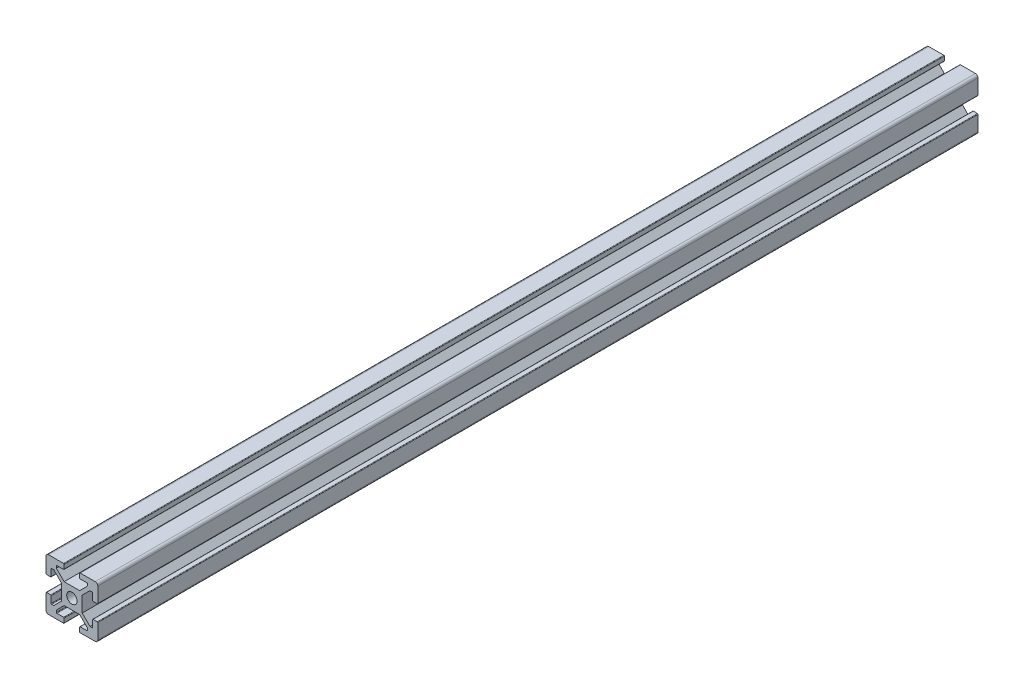
SolidWorks part; units mm, degrees
material "1060 Alloy"
ref_plane "Front Plane" through (0, 0, 0) normal (0, 0, 1) x (1, 0, 0)
ref_plane "Top Plane" through (0, 0, 0) normal (0, 1, 0) x (1, 0, 0)
ref_plane "Right Plane" through (0, 0, 0) normal (1, 0, 0) x (0, 0, -1)
sketch "Sketch1" plane through (0, 0, 0) normal (0, 0, 1) x (1, 0, 0)
  circle A28 centre (0, 0) radius 2
  point P0 (0, 0)
  line B0 (-3.2, 8) -> (-5.8005, 8)
  line B1 (-6.0005, 7.8005) -> (-6.0027, 7.0027)
  line B2 (-6.0027, 7.0027) -> (-3, 4)
  line B3 (-3, 4) -> (3, 4)
  line B4 (3, 4) -> (6.0027, 7.0027)
  line B5 (6.0027, 7.0027) -> (6.0005, 7.8005)
  line B6 (5.8005, 8) -> (3.2, 8)
  line B7 (3, 8.2) -> (3, 9.8)
  line B8 (3.2, 10) -> (9, 10)
  line B9 (10, 9) -> (10, 3.2)
  line B10 (9.8, 3) -> (8.2, 3)
  line B11 (8, 3.2) -> (8, 5.8005)
  line B12 (7.8005, 6.0005) -> (7.0027, 6.0027)
  line B13 (7.0027, 6.0027) -> (4, 3)
  line B14 (4, 3) -> (4, -3)
  line B15 (4, -3) -> (7.0027, -6.0027)
  line B16 (7.0027, -6.0027) -> (7.8005, -6.0005)
  line B17 (8, -5.8005) -> (8, -3.2)
  line B18 (8.2, -3) -> (9.8, -3)
  line B19 (10, -3.2) -> (10, -9)
  line B20 (9, -10) -> (3.2, -10)
  line B21 (3, -9.8) -> (3, -8.2)
  line B22 (3.2, -8) -> (5.8005, -8)
  line B23 (6.0005, -7.8005) -> (6.0027, -7.0027)
  line B24 (6.0027, -7.0027) -> (3, -4)
  line B25 (3, -4) -> (-3, -4)
  line B26 (-3, -4) -> (-6.0027, -7.0027)
  line B27 (-6.0027, -7.0027) -> (-6.0005, -7.8005)
  line B28 (-5.8005, -8) -> (-3.2, -8)
  line B29 (-3, -8.2) -> (-3, -9.8)
  line B30 (-3.2, -10) -> (-9, -10)
  line B31 (-10, -9) -> (-10, -3.2)
  line B32 (-9.8, -3) -> (-8.2, -3)
  line B33 (-8, -3.2) -> (-8, -5.8005)
  line B34 (-7.8005, -6.0005) -> (-7.0027, -6.0027)
  line B35 (-7.0027, -6.0027) -> (-4, -3)
  line B36 (-4, -3) -> (-4, 3)
  line B37 (-4, 3) -> (-7.0027, 6.0027)
  line B38 (-7.0027, 6.0027) -> (-7.8005, 6.0005)
  line B39 (-8, 5.8005) -> (-8, 3.2)
  line B40 (-8.2, 3) -> (-9.8, 3)
  line B41 (-10, 3.2) -> (-10, 9)
  line B42 (-9, 10) -> (-3.2, 10)
  line B43 (-3, 9.8) -> (-3, 8.2)
  line B44 (0, -4) -> (0, 4) construction
  line B45 (-4, 0) -> (4, 0) construction
  arc B46 (-5.8005, 8) -> (-6.0005, 7.8005) centre (-5.8005, 7.8) ccw
  arc B47 (6.0005, 7.8005) -> (5.8005, 8) centre (5.8005, 7.8) ccw
  arc B48 (3, 8.2) -> (3.2, 8) centre (3.2, 8.2) ccw
  arc B49 (3.2, 10) -> (3, 9.8) centre (3.2, 9.8) ccw
  arc B50 (10, 9) -> (9, 10) centre (9, 9) ccw
  arc B51 (9.8, 3) -> (10, 3.2) centre (9.8, 3.2) ccw
  arc B52 (8, 3.2) -> (8.2, 3) centre (8.2, 3.2) ccw
  arc B53 (8, 5.8005) -> (7.8005, 6.0005) centre (7.8, 5.8005) ccw
  arc B54 (7.8005, -6.0005) -> (8, -5.8005) centre (7.8, -5.8005) ccw
  arc B55 (8.2, -3) -> (8, -3.2) centre (8.2, -3.2) ccw
  arc B56 (10, -3.2) -> (9.8, -3) centre (9.8, -3.2) ccw
  arc B57 (9, -10) -> (10, -9) centre (9, -9) ccw
  arc B58 (3, -9.8) -> (3.2, -10) centre (3.2, -9.8) ccw
  arc B59 (3.2, -8) -> (3, -8.2) centre (3.2, -8.2) ccw
  arc B60 (5.8005, -8) -> (6.0005, -7.8005) centre (5.8005, -7.8) ccw
  arc B61 (-6.0005, -7.8005) -> (-5.8005, -8) centre (-5.8005, -7.8) ccw
  arc B62 (-3, -8.2) -> (-3.2, -8) centre (-3.2, -8.2) ccw
  arc B63 (-3.2, -10) -> (-3, -9.8) centre (-3.2, -9.8) ccw
  arc B64 (-10, -9) -> (-9, -10) centre (-9, -9) ccw
  arc B65 (-9.8, -3) -> (-10, -3.2) centre (-9.8, -3.2) ccw
  arc B66 (-8, -3.2) -> (-8.2, -3) centre (-8.2, -3.2) ccw
  arc B67 (-8, -5.8005) -> (-7.8005, -6.0005) centre (-7.8, -5.8005) ccw
  arc B68 (-7.8005, 6.0005) -> (-8, 5.8005) centre (-7.8, 5.8005) ccw
  arc B69 (-8.2, 3) -> (-8, 3.2) centre (-8.2, 3.2) ccw
  arc B70 (-10, 3.2) -> (-9.8, 3) centre (-9.8, 3.2) ccw
  arc B71 (-9, 10) -> (-10, 9) centre (-9, 9) ccw
  arc B72 (-3, 9.8) -> (-3.2, 10) centre (-3.2, 9.8) ccw
  arc B73 (-3.2, 8) -> (-3, 8.2) centre (-3.2, 8.2) ccw
  dimension "D1" = 4
sketch_block_instance "Block1-1"
sketch_block "Block1"
extrude "Boss-Extrude1" add sketch "Sketch1" along normal blind 340
